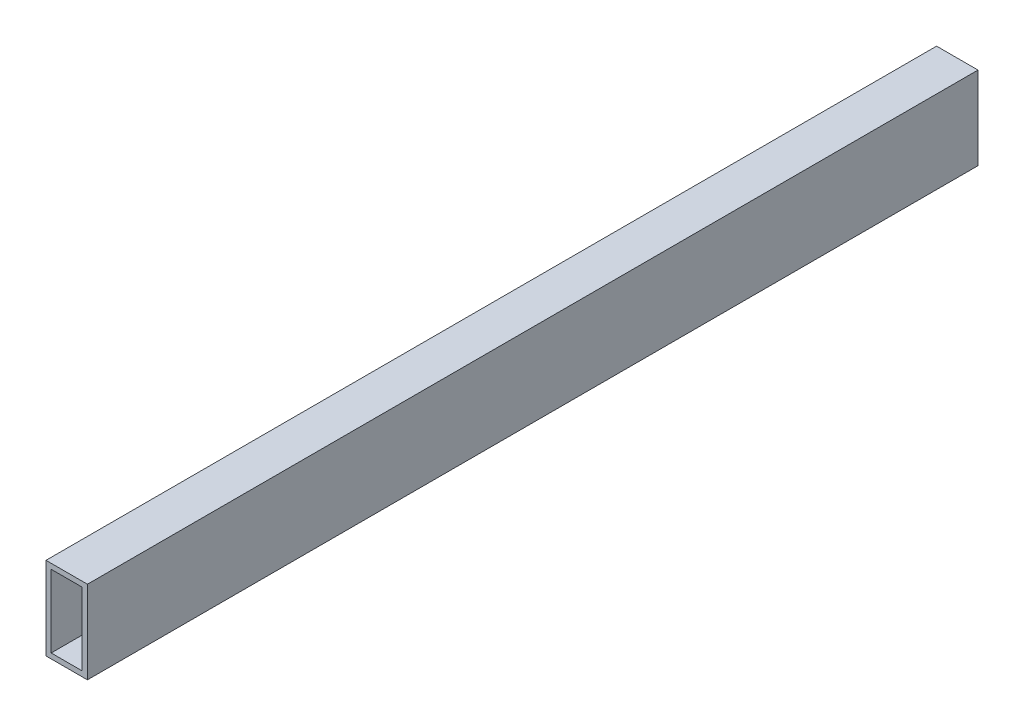
SolidWorks part; units mm, degrees
ref_plane "Front Plane" through (0, 0, 0) normal (0, 0, 1) x (1, 0, 0)
ref_plane "Top Plane" through (0, 0, 0) normal (0, 1, 0) x (1, 0, 0)
ref_plane "Right Plane" through (0, 0, 0) normal (1, 0, 0) x (0, 0, -1)
sketch "Sketch1" plane through (0, 0, 0) normal (0, 0, 1) x (1, 0, 0)
  line L1 (-12.7, 25.4) -> (12.7, 25.4)
  line L2 (-12.7, 25.4) -> (-12.7, -25.4)
  line L3 (-12.7, -25.4) -> (12.7, -25.4)
  line L4 (12.7, 25.4) -> (12.7, -25.4)
  line L5 (-12.7, 25.4) -> (12.7, -25.4) construction
  line L6 (-12.7, -25.4) -> (12.7, 25.4) construction
  line L7 (-9.525, 22.225) -> (9.525, 22.225)
  line L8 (-9.525, 22.225) -> (-9.525, -22.225)
  line L9 (-9.525, -22.225) -> (9.525, -22.225)
  line L10 (9.525, 22.225) -> (9.525, -22.225)
  line L11 (-9.525, 22.225) -> (9.525, -22.225) construction
  line L12 (-9.525, -22.225) -> (9.525, 22.225) construction
  point P0 (0, 0)
  point P5 (0, 0)
  dimension "D1" = 50.8
  dimension "D2" = 25.4
  dimension "D3" = 44.45
  dimension "D4" = 19.05
extrude "Boss-Extrude1" add sketch "Sketch1" along normal blind 546.1
